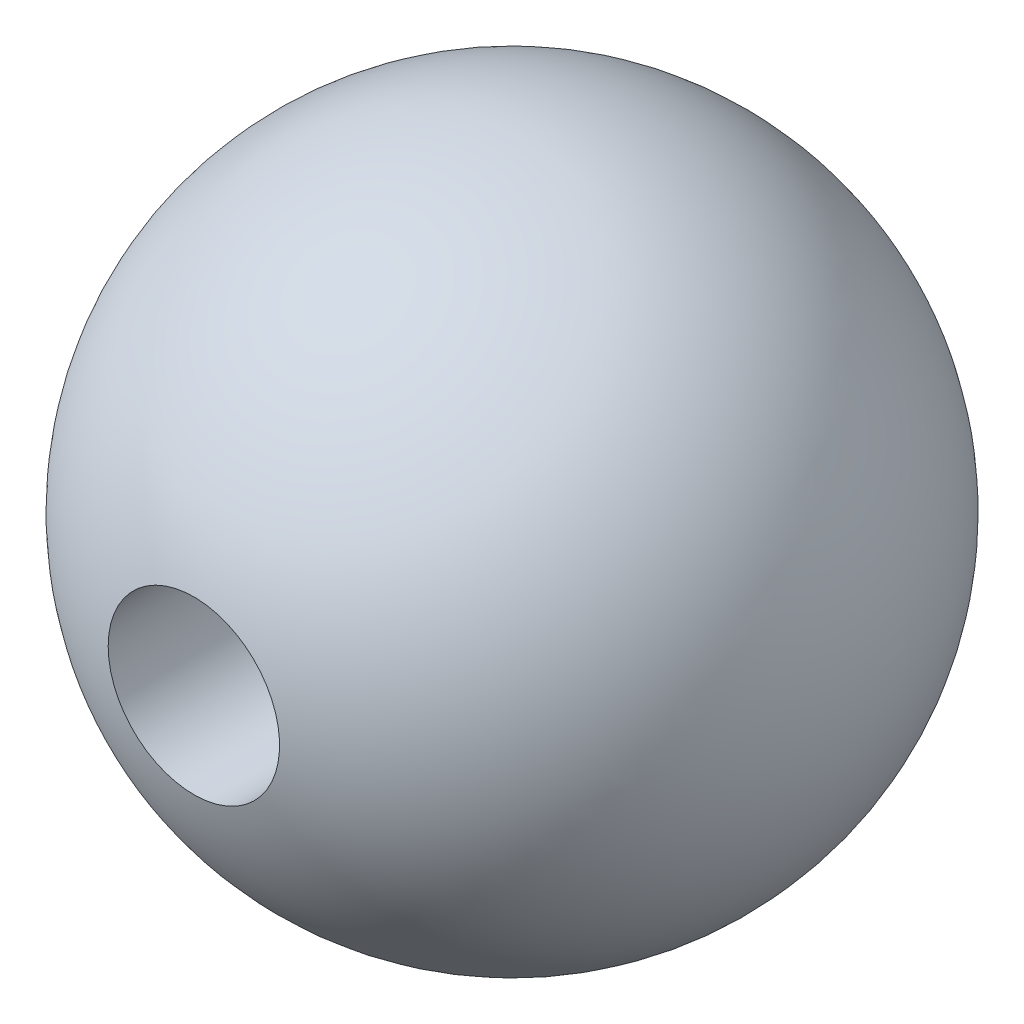
SolidWorks part; units mm, degrees
ref_plane "Front Plane" through (0, 0, 0) normal (0, 0, 1) x (1, 0, 0)
ref_plane "Top Plane" through (0, 0, 0) normal (0, 1, 0) x (1, 0, 0)
ref_plane "Right Plane" through (0, 0, 0) normal (1, 0, 0) x (0, 0, -1)
sketch "Sketch1" plane through (0, 0, 0) normal (0, 0, 1) x (1, 0, 0)
  line L0 (0, 0) -> (0, 12.7) construction
  line L1 (0, 12.7) -> (0, -12.7)
  arc A1 (0, 12.7) -> (0, -12.7) centre (0, 0) ccw
  dimension "D1" = 12.7
revolve "Revolve3" add sketch "Sketch1" angle 360 about L0
sketch "Sketch2" plane through (0, 0, 0) normal (0, 0, 1) x (1, 0, 0)
  circle A0 centre (0, 0) radius 3.302
  dimension "D1" = 6.604
extrude "Cut-Extrude1" cut sketch "Sketch2" against normal through all both and the other way through all
